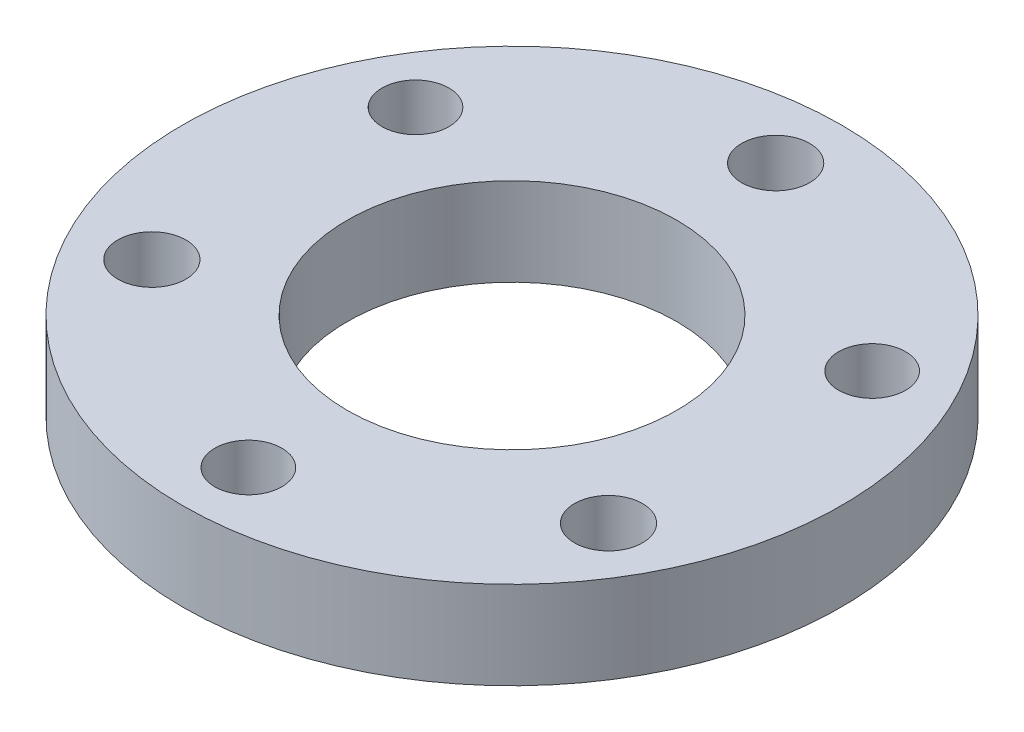
SolidWorks part; units mm, degrees
material "6061 合金"
ref_plane "前视基准面" through (0, 0, 0) normal (0, 0, 1) x (1, 0, 0)
ref_plane "上视基准面" through (0, 0, 0) normal (0, 1, 0) x (1, 0, 0)
ref_plane "右视基准面" through (0, 0, 0) normal (1, 0, 0) x (0, 0, -1)
sketch "草图1" plane through (0, 0, 0) normal (0, 1, 0) x (1, 0, 0)
  line L0 (-10.3923, 6) -> (0, 0) construction
  line L1 (0, 0) -> (-15, 0) construction
  circle A0 centre (0, 0) radius 15
  circle A1 centre (0, 0) radius 12 construction
  circle A2 centre (0, 12) radius 1.55
  circle A3 centre (10.3923, -6) radius 1.55
  circle A4 centre (-10.3923, -6) radius 1.55
  circle A5 centre (0, 0) radius 7.5
  circle A6 centre (-10.3923, 6) radius 1.525
  circle A7 centre (10.3923, 6) radius 1.525
  circle A8 centre (0, -12) radius 1.525
  dimension "D1" = 30
  dimension "D2" = 24
  dimension "D3" = 3.1
  dimension "D5" = 15
  dimension "D6" = 3.05
  dimension "D7" = 30
  dimension "D4" = 3
  dimension "D8" = 3
extrude "凸台-拉伸1" add sketch "草图1" along normal blind 4
